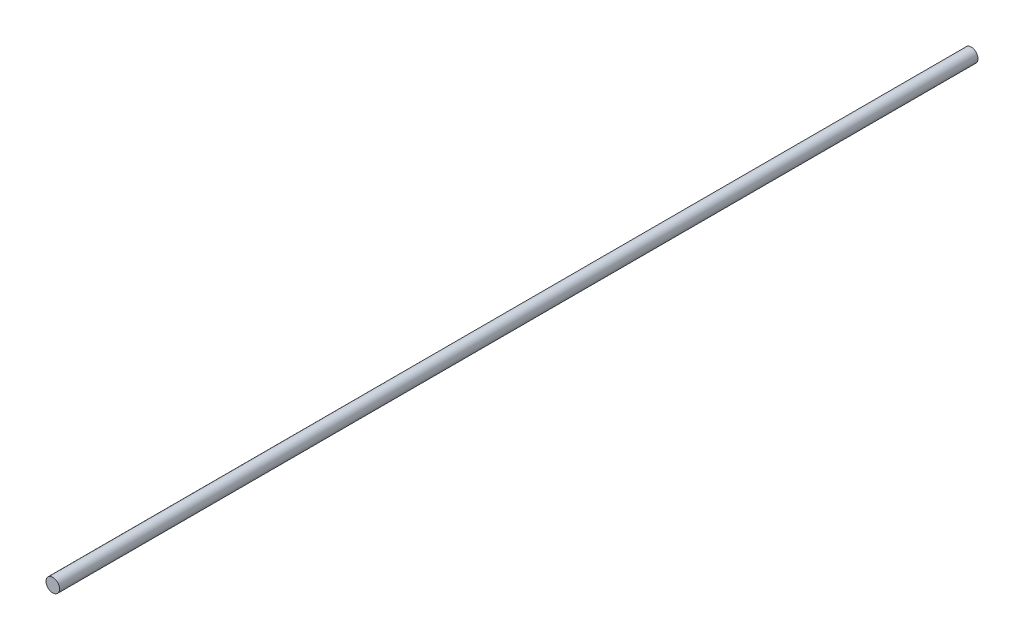
SolidWorks part; units mm, degrees
ref_plane "Alzado" through (0, 0, 0) normal (0, 0, 1) x (1, 0, 0)
ref_plane "Planta" through (0, 0, 0) normal (0, 1, 0) x (1, 0, 0)
ref_plane "Vista lateral" through (0, 0, 0) normal (1, 0, 0) x (0, 0, -1)
sketch "Croquis1" plane through (0, 0, 0) normal (0, 0, 1) x (1, 0, 0)
  circle A0 centre (-7.1402, 7.661) radius 4.3
  dimension "D1" = 8.6
extrude "Saliente-Extruir1" add sketch "Croquis1" along normal blind 583
